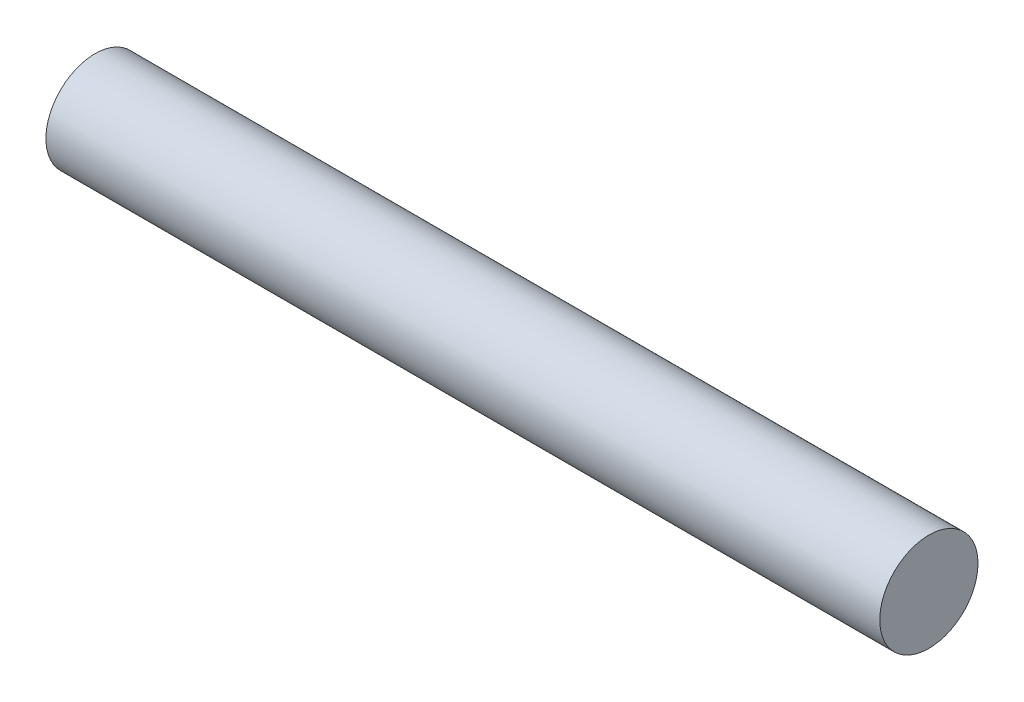
SolidWorks part; units mm, degrees
material "6061 Alloy"
ref_plane "Front Plane" through (0, 0, 0) normal (0, 0, 1) x (1, 0, 0)
ref_plane "Top Plane" through (0, 0, 0) normal (0, 1, 0) x (1, 0, 0)
ref_plane "Right Plane" through (0, 0, 0) normal (1, 0, 0) x (0, 0, -1)
sketch "Sketch1" plane through (0, 0, 0) normal (1, 0, 0) x (0, 0, -1)
  circle A0 centre (0, 0) radius 4
  dimension "D1" = 8
extrude "Boss-Extrude1" add sketch "Sketch1" along normal blind 67.9
